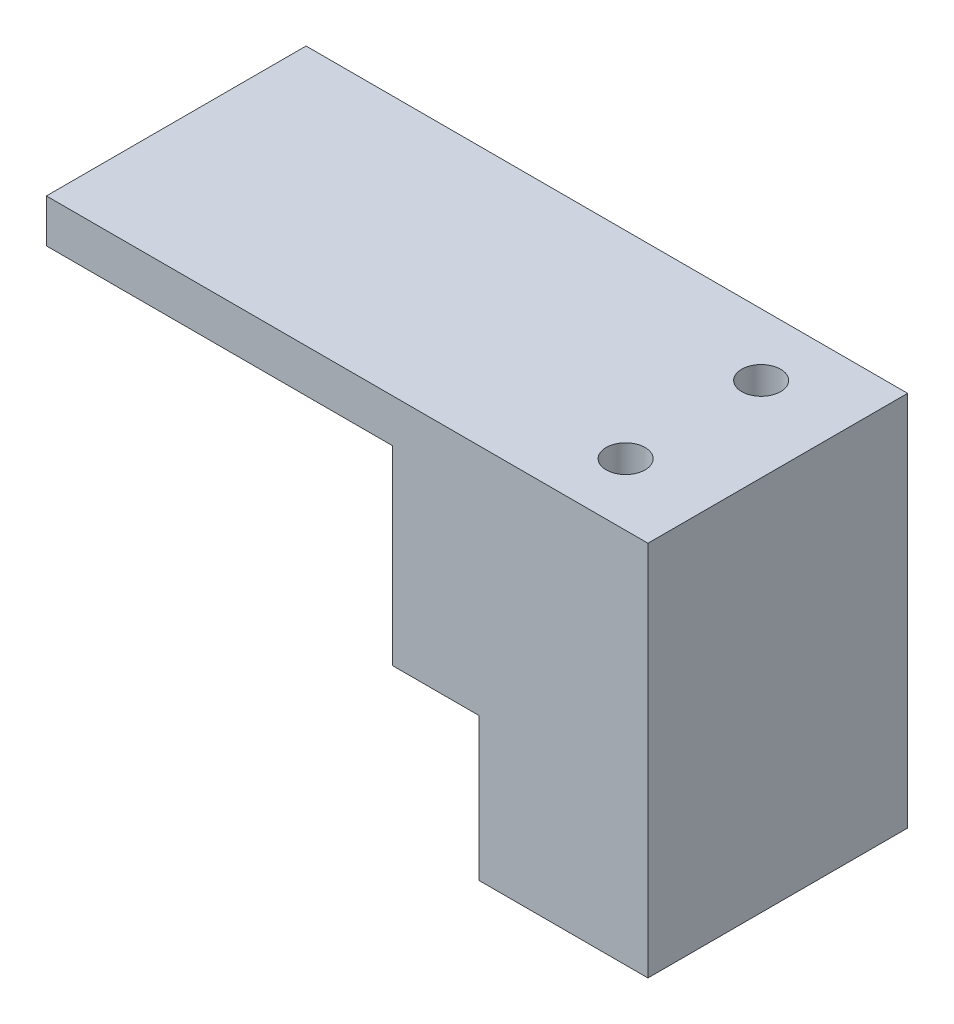
SolidWorks part; units mm, degrees
ref_plane "Front Plane" through (0, 0, 0) normal (0, 0, 1) x (1, 0, 0)
ref_plane "Top Plane" through (0, 0, 0) normal (0, 1, 0) x (1, 0, 0)
ref_plane "Right Plane" through (0, 0, 0) normal (1, 0, 0) x (0, 0, -1)
sketch "Sketch1" plane through (0, 0, 0) normal (0, 1, 0) x (1, 0, 0)
  line L0 (9.75, 0) -> (9.75, 7.1699) construction
  line L1 (0, 0) -> (19.5, 0)
  line L2 (0, 0) -> (0, 30)
  line L3 (0, 30) -> (19.5, 30)
  line L4 (19.5, 0) -> (19.5, 30)
  line L5 (9.75, 7.1699) -> (9.75, 22.8301) construction
  line L6 (9.75, 22.8301) -> (9.75, 30) construction
  circle A0 centre (9.75, 22.8301) radius 2.25
  circle A1 centre (9.75, 7.1699) radius 2.25
  dimension "D3" = 4.5
  dimension "D1" = 19.5
  dimension "D2" = 30
extrude "Boss-Extrude1" add sketch "Sketch1" along normal blind 16.5
sketch "Sketch2" plane through (0, 16.5, 0) normal (0, 1, 0) x (1, 0, 0)
  line L0 (0, 30) -> (-10, 30)
  line L1 (-10, 30) -> (-10, 0)
  line L2 (-10, 0) -> (0, 0)
  line L4 (0, 30) -> (0, 0)
  line L5 (0, 0) -> (19.5, 0)
  line L6 (19.5, 0) -> (19.5, 30)
  line L7 (19.5, 30) -> (0, 30)
  line L9 (0, 0) -> (19.5, 0)
  line L10 (19.5, 0) -> (19.5, 30)
  line L11 (19.5, 30) -> (0, 30)
  circle A0 centre (9.75, 22.8301) radius 2.25
  circle A1 centre (9.75, 7.1699) radius 2.25
  dimension "D2" = 10
  dimension "D1" = 0
extrude "Boss-Extrude2" add sketch "Sketch2" along normal blind 22
sketch "Sketch3" plane through (0, 38.5, 0) normal (0, 1, 0) x (1, 0, 0)
  line L0 (-10, 30) -> (-50, 30)
  line L1 (-50, 30) -> (-50, 0)
  line L2 (-50, 0) -> (-10, 0)
  line L4 (19.5, 30) -> (-10, 30)
  line L5 (-10, 30) -> (-10, 0)
  line L6 (-10, 0) -> (19.5, 0)
  line L7 (19.5, 0) -> (19.5, 30)
  line L8 (19.5, 30) -> (-10, 30)
  line L10 (-10, 0) -> (19.5, 0)
  line L11 (19.5, 0) -> (19.5, 30)
  circle A0 centre (9.75, 22.8301) radius 2.25
  circle A1 centre (9.75, 7.1699) radius 2.25
  dimension "D2" = 40
  dimension "D1" = 0
extrude "Boss-Extrude3" add sketch "Sketch3" along normal blind 5
